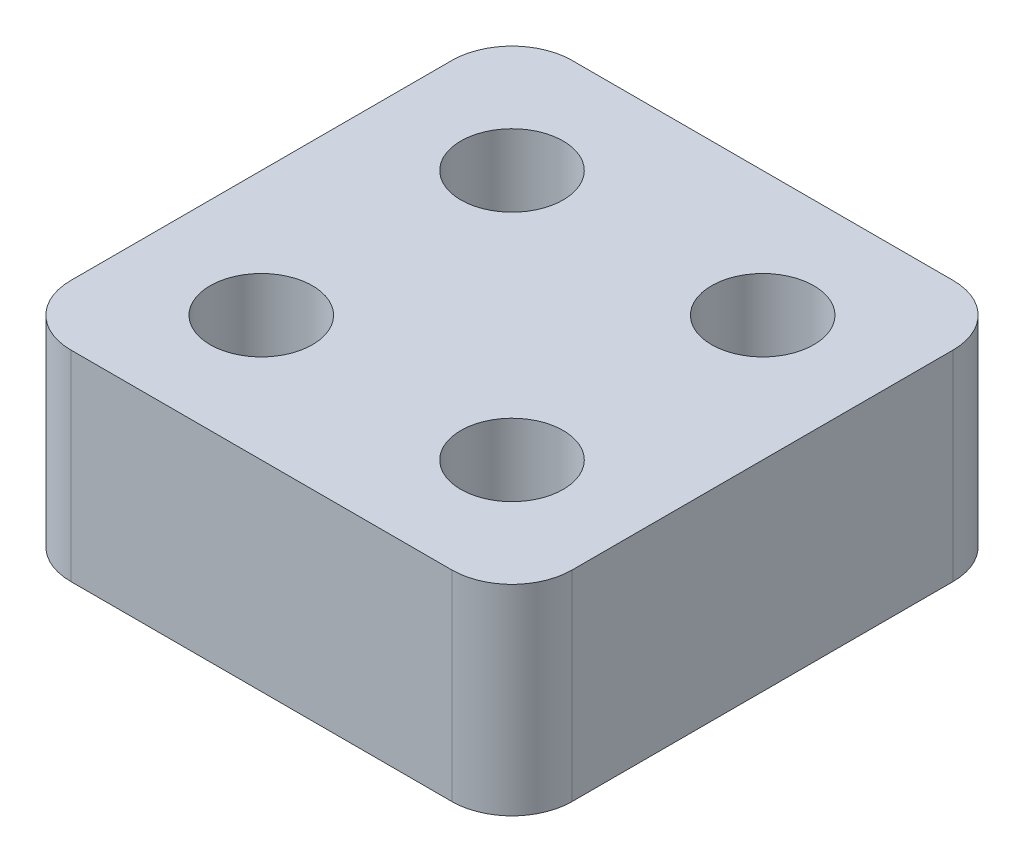
SolidWorks part; units mm, degrees
ref_plane "前视基准面" through (0, 0, 0) normal (0, 0, 1) x (1, 0, 0)
ref_plane "上视基准面" through (0, 0, 0) normal (0, 1, 0) x (1, 0, 0)
ref_plane "右视基准面" through (0, 0, 0) normal (1, 0, 0) x (0, 0, -1)
sketch "草图1" plane through (0, 0, 0) normal (0, 1, 0) x (1, 0, 0)
  line L1 (-9.5, 12.5) -> (9.5, 12.5)
  line L2 (-12.5, 9.5) -> (-12.5, -9.5)
  line L3 (-9.5, -12.5) -> (9.5, -12.5)
  line L4 (12.5, 9.5) -> (12.5, -9.5)
  line L5 (-12.5, 12.5) -> (12.5, -12.5) construction
  line L6 (-12.5, -12.5) -> (12.5, 12.5) construction
  arc A0 (-12.5, -9.5) -> (-9.5, -12.5) centre (-9.5, -9.5) ccw
  arc A1 (9.5, -12.5) -> (12.5, -9.5) centre (9.5, -9.5) ccw
  arc A2 (9.5, 12.5) -> (12.5, 9.5) centre (9.5, 9.5) cw
  arc A3 (-9.5, 12.5) -> (-12.5, 9.5) centre (-9.5, 9.5) ccw
  circle A4 centre (0, 0) radius 8.8388 construction
  circle A5 centre (-6.25, 6.25) radius 2.55
  circle A6 centre (6.25, 6.25) radius 2.55
  circle A7 centre (-6.25, -6.25) radius 2.55
  circle A8 centre (6.25, -6.25) radius 2.55
  point P0 (0, 0)
  dimension "D1" = 3
  dimension "D2" = 5.1
  dimension "D3" = 12.5
  dimension "D4" = 25
extrude "凸台-拉伸1" add sketch "草图1" along normal blind 10
